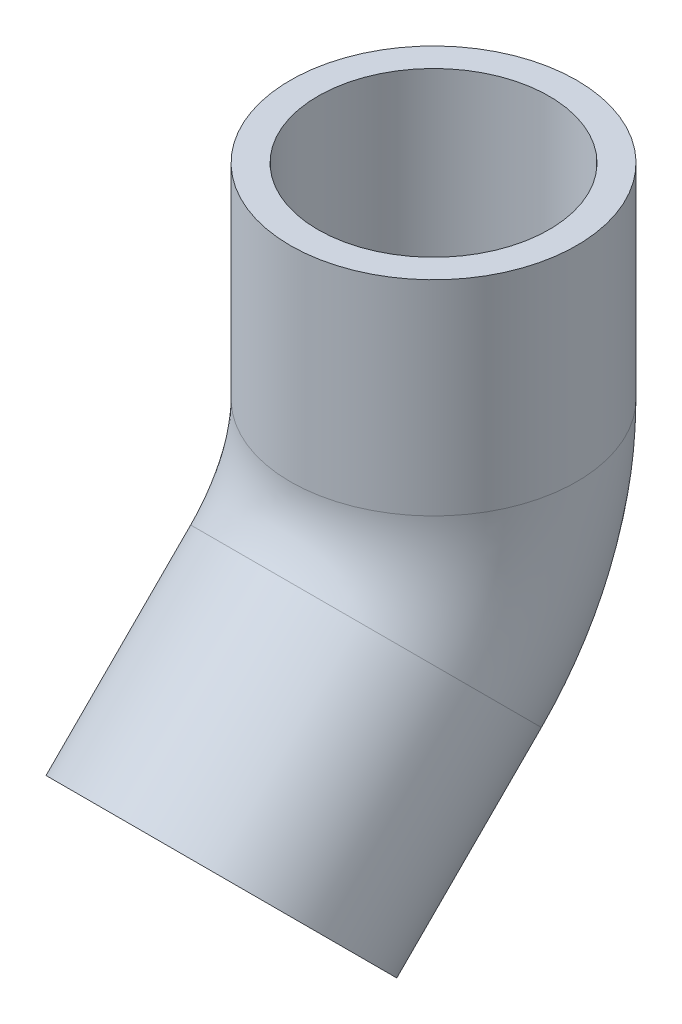
SolidWorks part; units mm, degrees
material "PVC Rigid"
ref_plane "Front Plane" through (0, 0, 0) normal (0, 0, 1) x (1, 0, 0)
ref_plane "Top Plane" through (0, 0, 0) normal (0, 1, 0) x (1, 0, 0)
ref_plane "Right Plane" through (0, 0, 0) normal (1, 0, 0) x (0, 0, -1)
sketch "Sketch1" plane through (0, 0, 0) normal (1, 0, 0) x (0, 0, -1)
  line L0 (0, 0) -> (0, 34.925) construction
  line L1 (0, 0) -> (-24.6957, -24.6957) construction
  line L2 (-13.462, 11.1125) -> (13.462, 11.1125) construction
  line L3 (-16.6688, 34.925) -> (16.6687, 34.925) construction
  line L4 (10.4648, 0) -> (-10.4648, 0) construction
  line L5 (-17.3768, 1.6613) -> (1.6613, -17.3768) construction
  line L6 (-36.4823, -12.9091) -> (-12.9091, -36.4823) construction
  point P7 (0, 11.1125)
  point P10 (0, 34.925)
  point P13 (0, 0)
  point P16 (-7.8577, -7.8577)
  point P19 (-24.6957, -24.6957)
  dimension "D1" = 45
  dimension "Leg Length" = 34.925
  dimension "Center to Socket" = 11.1125
  dimension "Elbow OD" = 33.3375
  dimension "For Pipe OD" = 26.924
  dimension "Pipe ID" = 20.9296
  dimension "D2" = 23.8125
  dimension "D3" = 11.1125
sketch "Sketch2" plane through (0, 0, 0) normal (1, 0, 0) x (0, 0, -1)
  line L0 (-24.6957, -24.6957) -> (-7.8577, -7.8577)
  line L1 (0, 0) -> (-24.6957, -24.6957) construction
  line L2 (0, 34.925) -> (0, 11.1125)
  line L3 (0, 0) -> (0, 34.925) construction
  line L4 (-13.462, 11.1125) -> (13.462, 11.1125) construction
  arc A0 (-7.8577, -7.8577) -> (0, 11.1125) centre (-26.8279, 11.1125) ccw
ref_plane "Plane1" through (0, 34.925, 0) normal (0, 1, 0) x (1, 0, 0)
sketch "Sketch3" plane through (0, 34.925, 0) normal (0, 1, 0) x (1, 0, 0)
  circle A0 centre (0, 0) radius 16.6687
  circle A1 centre (0, 0) radius 10.4648
  dimension "D1" = 33.3375
  dimension "D2" = 20.9296
sweep "Sweep1" add profiles "Sketch3" path "Sketch2"
sketch "Sketch4" plane through (0, 34.925, 0) normal (0, 1, 0) x (1, 0, 0)
  circle A0 centre (0, 0) radius 13.462
  dimension "D1" = 26.924
extrude "Cut-Extrude1" cut sketch "Sketch4" against normal blind 23.8125
sketch "Sketch5" plane through (0, -24.6957, 24.6957) normal (0, -0.7071, 0.7071) x (1, 0, 0)
  circle A0 centre (0, 0) radius 13.462
  dimension "D1" = 26.924
extrude "Cut-Extrude2" cut sketch "Sketch5" against normal blind 23.8125
sketch "Sketch6" plane through (0, 0, 0) normal (1, 0, 0) x (0, 0, -1)
  line L0 (1.6613, -17.3768) -> (-15.1766, -34.2148) construction
  line L1 (-17.3768, 1.6613) -> (-34.2148, -15.1766) construction
  line L2 (-36.4823, -12.9091) -> (-12.9091, -36.4823) construction
  line L3 (13.462, 11.1125) -> (13.462, 34.925) construction
  line L4 (-13.462, 11.1125) -> (-13.462, 34.925) construction
  line L5 (-16.6688, 34.925) -> (16.6687, 34.925) construction
  line L6 (-13.462, 11.1125) -> (-10.4648, 11.1125) construction
  line L7 (-13.462, 11.1125) -> (13.462, 11.1125) construction
  line L8 (13.462, 11.1125) -> (10.4648, 11.1125) construction
  line L9 (-17.3768, 1.6613) -> (-15.2575, -0.458) construction
  line L10 (-17.3768, 1.6613) -> (1.6613, -17.3768) construction
  line L11 (1.6613, -17.3768) -> (-0.458, -15.2575) construction
  arc A0 (-10.4648, 11.1125) -> (-15.2575, -0.458) centre (-26.8279, 11.1125) cw construction
  arc A1 (-0.458, -15.2575) -> (10.4648, 11.1125) centre (-26.8279, 11.1125) ccw construction
  arc A2 (-7.8577, -7.8577) -> (0, 11.1125) centre (-26.8279, 11.1125) ccw construction
sketch "Sketch7" plane through (0, -24.6957, 24.6957) normal (0, -0.7071, 0.7071) x (1, 0, 0)
  circle A0 centre (0, 0) radius 13.462 construction
  circle A1 centre (0, 0) radius 13.462 construction
  circle A2 centre (0, 0) radius 16.6688 construction
  circle A3 centre (0, 0) radius 16.6687 construction
  point P3 (0, -13.462)
  point P4 (13.462, 0)
  point P5 (0, 13.462)
  point P6 (-13.462, 0)
  point P9 (0, -16.6687)
  point P10 (16.6687, 0)
  point P11 (-16.6687, 0)
  point P12 (0, 16.6687)
equation "\"D1@Sketch3\"=\"Elbow OD@Sketch1\""
equation "\"D2@Sketch3\"=\"Pipe ID@Sketch1\""
equation "\"D1@Sketch4\"=\"For Pipe OD@Sketch1\""
equation "\"D1@Cut-Extrude1\"=\"D2@Sketch1\""
equation "\"D1@Sketch5\"=\"For Pipe OD@Sketch1\""
equation "\"D1@Cut-Extrude2\"=\"D2@Sketch1\""
equation "\"D3@Sketch1\"=\"Center to Socket@Sketch1\""
